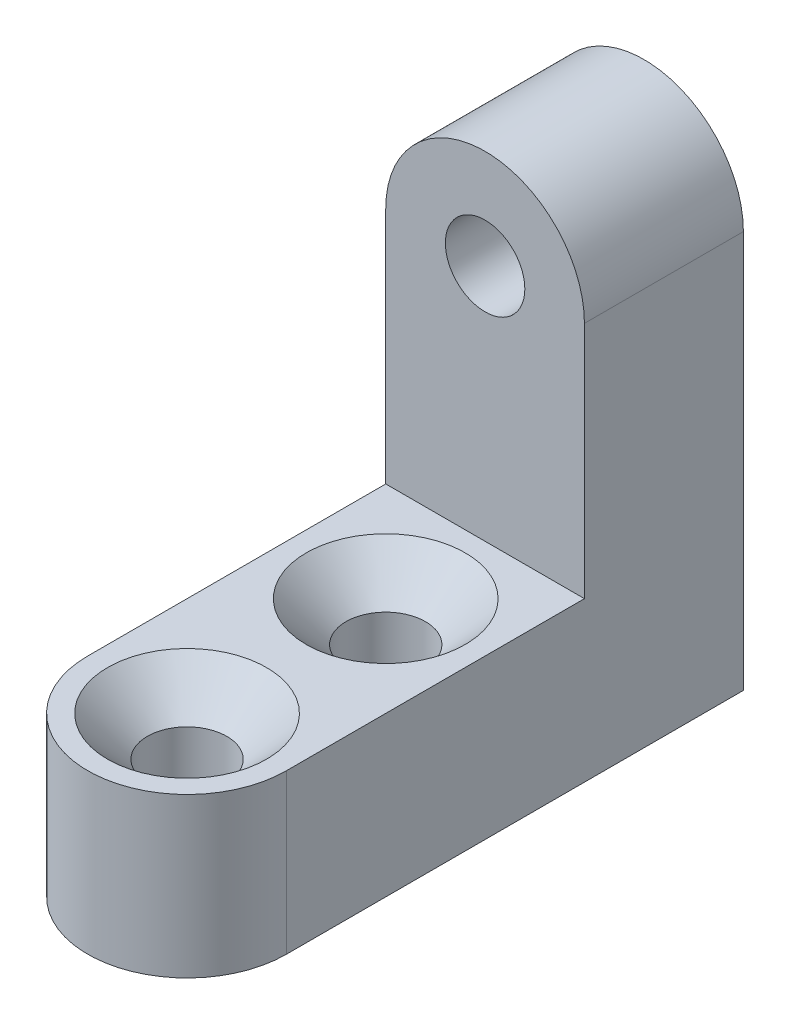
SolidWorks part; units mm, degrees
material "1060 合金"
ref_plane "前视基准面" through (0, 0, 0) normal (0, 0, 1) x (1, 0, 0)
ref_plane "上视基准面" through (0, 0, 0) normal (0, 1, 0) x (1, 0, 0)
ref_plane "右视基准面" through (0, 0, 0) normal (1, 0, 0) x (0, 0, -1)
sketch "草图1" plane through (0, 0, 0) normal (0, 0, 1) x (1, 0, 0)
  line L2 (-5, 20) -> (-5, 0)
  line L3 (-5, 0) -> (5, 0)
  line L4 (5, 20) -> (5, 0)
  arc A0 (5, 20) -> (-5, 20) centre (0, 20) ccw
  circle A1 centre (0, 20) radius 2
  point P1 (0, 0)
  dimension "D1" = 5
  dimension "D2" = 4
  dimension "D3" = 20
extrude "凸台-拉伸1" add sketch "草图1" along normal blind 8
sketch "草图2" plane through (0, 0, 0) normal (0, 1, 0) x (1, 0, 0)
  line L1 (-5, -8) -> (5, -8)
  line L2 (-5, -8) -> (-5, -23)
  line L4 (5, -8) -> (5, -23)
  circle A0 centre (0, -23) radius 2
  arc A1 (-5, -23) -> (5, -23) centre (0, -23) ccw
  circle A2 centre (0, -13) radius 2
  dimension "D1" = 4
  dimension "D2" = 15
  dimension "D3" = 10
extrude "凸台-拉伸2" add sketch "草图2" along normal blind 8
chamfer "倒角1" distance 2 angle 45 2 edges at (0, 8, 25) (0, 8, 15)
